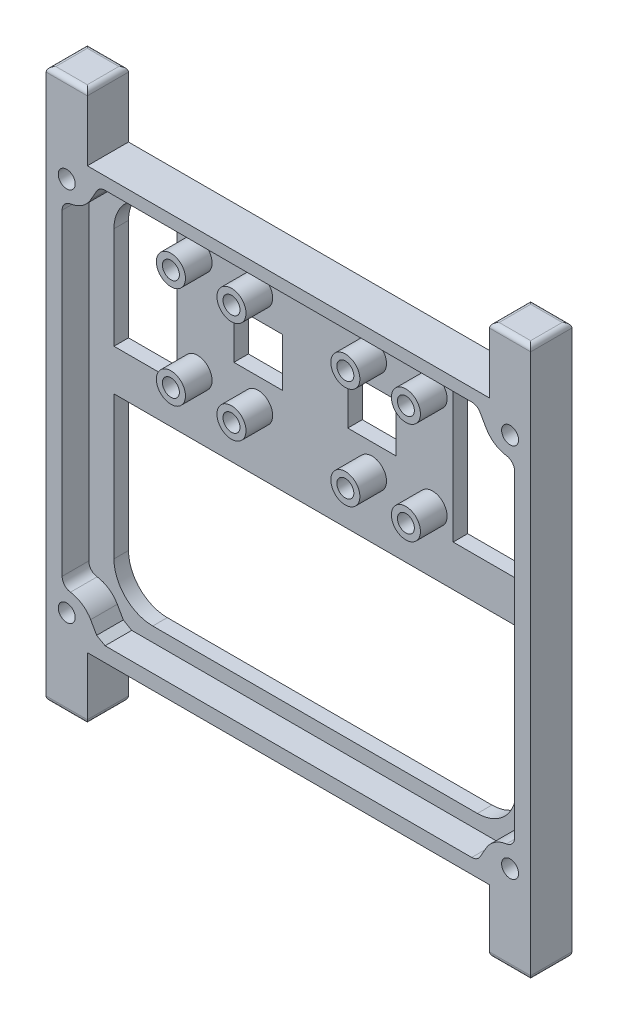
SolidWorks part; units mm, degrees
ref_plane "Front Plane" through (0, 0, 0) normal (0, 0, 1) x (1, 0, 0)
ref_plane "Top Plane" through (0, 0, 0) normal (0, 1, 0) x (1, 0, 0)
ref_plane "Right Plane" through (0, 0, 0) normal (1, 0, 0) x (0, 0, -1)
sketch "Sketch1" plane through (0, 0, 0) normal (0, 0, 1) x (1, 0, 0)
  line L1 (-50, 56.75) -> (50, 56.75)
  line L2 (-50, 56.75) -> (-50, -56.75)
  line L3 (-50, -56.75) -> (50, -56.75)
  line L4 (50, 56.75) -> (50, -56.75)
  line L5 (-50, 56.75) -> (50, -56.75) construction
  line L6 (-50, -56.75) -> (50, 56.75) construction
  point P0 (0, 0)
  dimension "D1" = 100
  dimension "D2" = 113.5
extrude "Boss-Extrude1" add sketch "Sketch1" along normal blind 8.5
sketch "Sketch2" plane through (0, 0, 8.5) normal (0, 0, 1) x (1, 0, 0)
  line L1 (50, 56.75) -> (-50, 56.75) construction
  line L2 (-41.5, 56.75) -> (-41.5, 43.25)
  line L3 (-50, -56.75) -> (50, -56.75) construction
  line L6 (0, -4.675) -> (0, 4.675) construction
  line L8 (41.5, 56.75) -> (41.5, 43.25)
  line L11 (-33.5, -37.75) -> (33.5, -37.75)
  line L12 (-41.5, 43.25) -> (41.5, 43.25)
  line L17 (-41.5, -0.25) -> (41.5, -0.25)
  line L18 (-41.5, -43.75) -> (41.5, -43.75)
  line L19 (-41.5, -29.75) -> (-41.5, -0.25)
  line L20 (41.5, -29.75) -> (41.5, -0.25)
  line L33 (41.5, -0.25) -> (41.5, -29.75)
  line L34 (-41.5, -0.25) -> (-41.5, -29.75)
  line L35 (-41.5, -43.75) -> (-41.5, -56.75)
  line L36 (41.5, -43.75) -> (41.5, -56.75)
  line L37 (-16.75, 27.75) -> (-6.75, 27.75)
  line L38 (-18.25, 29.25) -> (-5.25, 29.25)
  line L39 (-18.25, 29.25) -> (-18.25, 16.25)
  line L40 (-18.25, 16.25) -> (-5.25, 16.25)
  line L41 (-5.25, 29.25) -> (-5.25, 16.25)
  line L42 (-18.25, 29.25) -> (-5.25, 16.25) construction
  line L43 (-18.25, 16.25) -> (-5.25, 29.25) construction
  line L44 (-6.75, 27.75) -> (-6.75, 17.75)
  line L45 (-16.75, 17.75) -> (-6.75, 17.75)
  line L46 (-16.75, 27.75) -> (-16.75, 17.75)
  line L47 (-41.5, -56.75) -> (41.5, -56.75)
  line L48 (-41.5, 56.75) -> (41.5, 56.75)
  line L49 (50, -56.75) -> (50, 56.75) construction
  line L50 (4.675, 0) -> (-4.675, 0) construction
  line L51 (0, 43.25) -> (0, 0) construction
  line L52 (-11.75, 35.783) -> (-11.75, 12.7164) construction
  line L57 (16.75, 27.75) -> (16.75, 17.75)
  line L58 (16.75, 17.75) -> (6.75, 17.75)
  line L59 (6.75, 27.75) -> (6.75, 17.75)
  line L60 (16.75, 27.75) -> (6.75, 27.75)
  line L61 (28.5, 37.25) -> (23.5, 37.25)
  line L62 (23.5, 37.25) -> (23.5, 11.25)
  line L63 (41.5, 11.25) -> (23.5, 11.25)
  line L64 (41.5, 24.25) -> (41.5, 11.25)
  line L65 (6.75, 27.75) -> (16.75, 27.75)
  line L66 (16.75, 17.75) -> (6.75, 17.75)
  line L67 (23.5, 37.25) -> (23.5, 11.25)
  line L68 (41.5, 11.25) -> (41.5, 24.25)
  line L69 (23.5, 37.25) -> (28.5, 37.25)
  arc A0 (41.5, -29.75) -> (33.5, -37.75) centre (33.5, -29.75) cw
  arc A1 (-41.5, -29.75) -> (-33.5, -37.75) centre (-33.5, -29.75) ccw
  circle A4 centre (45.75, 38.75) radius 1.75
  circle A5 centre (45.75, -38.75) radius 1.75
  circle A6 centre (-45.75, 38.75) radius 1.75
  circle A7 centre (-45.75, -38.75) radius 1.75
  arc A8 (41.5, 24.25) -> (28.5, 37.25) centre (28.5, 24.25) ccw
  arc A9 (28.5, 37.25) -> (41.5, 24.25) centre (28.5, 24.25) cw
  point P0 (45.75, 38.75)
  point P22 (-11.75, 22.75)
  point P63 (-11.75, 22.75)
  dimension "D2" = 13
  dimension "D3" = 13.5
  dimension "D6" = 113.5
  dimension "D8" = 6
  dimension "D11" = 13
  dimension "D12" = 13
  dimension "D14" = 18
  dimension "D15" = 4.25
  dimension "D13" = 1.5
extrude "Cut-Extrude1" cut sketch "Sketch2" against normal up to next
ref_plane "Plane1" through (0, 0, 3) normal (0, 0, -1) x (-1, 0, 0)
sketch "Sketch6" plane through (0, 0, 8.5) normal (0, 0, 1) x (1, 0, 0)
  line L8 (50, -56.75) -> (50, 56.75) construction
  line L10 (41.5, 8.25) -> (41.5, 29.25)
  line L11 (33.5, 8.25) -> (41.5, 8.25)
  line L14 (6.75, 17.75) -> (16.75, 17.75)
  line L15 (6.75, 27.75) -> (6.75, 17.75)
  line L16 (16.75, 27.75) -> (6.75, 27.75)
  line L17 (16.75, 17.75) -> (16.75, 27.75)
  line L21 (33.5, 37.25) -> (28.5, 37.25)
  line L22 (28.5, 37.25) -> (28.5, 8.25)
  line L23 (28.5, 8.25) -> (33.5, 8.25)
  line L24 (0, -4.675) -> (0, 4.675) construction
  line L25 (-41.5, 8.25) -> (-41.5, 29.25)
  line L26 (-33.5, 8.25) -> (-41.5, 8.25)
  line L27 (-28.5, 8.25) -> (-33.5, 8.25)
  line L28 (-28.5, 37.25) -> (-28.5, 8.25)
  line L29 (-33.5, 37.25) -> (-28.5, 37.25)
  arc A1 (41.5, 29.25) -> (33.5, 37.25) centre (33.5, 29.25) ccw
  arc A2 (-41.5, 29.25) -> (-33.5, 37.25) centre (-33.5, 29.25) cw
  dimension "D1" = 8.5
  dimension "D2" = 5
extrude "Cut-Extrude2" cut sketch "Sketch6" against normal up to next
sketch "Sketch8" plane through (0, 0, 8.5) normal (0, 0, 1) x (1, 0, 0)
  line L0 (-37.835, -40.7) -> (37.835, -40.7)
  line L1 (-41.5, -43.75) -> (41.5, -43.75) construction
  line L2 (-37.835, -40.7) -> (-39.5671, -39.7)
  line L3 (-39.5671, -39.7) -> (-40.8111, -37.52)
  line L4 (0, -4.675) -> (0, 4.675) construction
  line L5 (39.5671, -39.7) -> (40.8111, -37.52)
  line L6 (4.675, 0) -> (-4.675, 0) construction
  line L7 (39.5671, 39.7) -> (40.8111, 37.52)
  line L8 (-39.5671, 39.7) -> (-40.8111, 37.52)
  line L9 (46.7011, 32.72) -> (46.7011, -32.72)
  line L10 (-46.7011, -32.72) -> (-46.7011, 32.72)
  line L11 (-37.835, 40.7) -> (37.835, 40.7)
  arc A0 (-39.5671, -39.7) -> (-37.835, -40.7) centre (-37.845, -38.7172) ccw
  arc A1 (-44.9811, -34.7) -> (-40.8111, -37.52) centre (-45.7922, -40.3925) cw
  arc A2 (-46.7011, -32.72) -> (-44.9811, -34.7) centre (-44.7011, -32.7197) ccw
  arc A3 (39.5671, -39.7) -> (37.835, -40.7) centre (37.845, -38.7172) cw
  arc A4 (44.9811, -34.7) -> (40.8111, -37.52) centre (45.7922, -40.3925) ccw
  arc A5 (46.7011, -32.72) -> (44.9811, -34.7) centre (44.7011, -32.7197) cw
  arc A6 (39.5671, 39.7) -> (37.835, 40.7) centre (37.845, 38.7172) ccw
  arc A7 (46.7011, 32.72) -> (44.9811, 34.7) centre (44.7011, 32.7197) ccw
  arc A8 (44.9811, 34.7) -> (40.8111, 37.52) centre (45.7922, 40.3925) cw
  arc A9 (-39.5671, 39.7) -> (-37.835, 40.7) centre (-37.845, 38.7172) cw
  arc A10 (-44.9811, 34.7) -> (-40.8111, 37.52) centre (-45.7922, 40.3925) ccw
  arc A11 (-46.7011, 32.72) -> (-44.9811, 34.7) centre (-44.7011, 32.7197) cw
  point P4 (0, -40.7)
  point P5 (0, -43.75)
  point P8 (-44.9811, -34.7)
  point P10 (-46.7011, -32.72)
  dimension "D5" = 2.51
  dimension "D9" = 1.98
  dimension "D1" = 3.05
  dimension "D2" = 75.67
  dimension "D3" = 2
  dimension "D4" = 1
  dimension "D6" = 2.18
  dimension "D7" = 2.82
  dimension "D8" = 4.17
  dimension "D10" = 1.72
extrude "Cut-Extrude4" cut sketch "Sketch8" against normal blind 5.5
sketch "Sketch7" plane through (0, 0, 8.5) normal (0, 0, 1) x (1, 0, 0)
  line L0 (-16.75, 27.75) -> (-6.75, 27.75) construction
  line L3 (0, 40.7) -> (0, 35.089)
  line L4 (-37.835, 40.7) -> (37.835, 40.7) construction
  circle A0 centre (-11.75, 33.25) radius 3
  circle A1 centre (-11.75, 33.25) radius 1.75
  circle A2 centre (-11.75, 12.25) radius 1.75
  circle A3 centre (-11.75, 12.25) radius 3
  circle A4 centre (11.75, 33.25) radius 1.75
  circle A5 centre (11.75, 33.25) radius 3
  circle A6 centre (11.75, 12.25) radius 1.75
  circle A7 centre (11.75, 12.25) radius 3
  circle A8 centre (-24.25, 33.25) radius 3
  circle A9 centre (-24.25, 33.25) radius 1.75
  circle A10 centre (-24.25, 12.25) radius 3
  circle A11 centre (-24.25, 12.25) radius 1.75
  circle A12 centre (24.25, 12.25) radius 1.75
  circle A13 centre (24.25, 12.25) radius 3
  circle A14 centre (24.25, 33.25) radius 1.75
  circle A15 centre (24.25, 33.25) radius 3
  point P0 (-11.75, 33.25)
  point P6 (-11.75, 27.75)
  point P25 (-24.25, 33.25)
  dimension "D2" = 12.5
  dimension "D1" = 5.5
extrude "Boss-Extrude3" add sketch "Sketch7" against normal blind 5.5 contours A8 A9 | A10 A11 | A3 A2 | A5 A4 | A15 A14 | A7 A6 | A13 A12 | A0 A1
fillet "Fillet1" radius 1 16 edges at (45.75, 56.75, 8.5) (50, 56.75, 4.25) (45.75, 56.75, 0) (41.5, 56.75, 4.25) (-41.5, 56.75, 4.25) (-45.75, 56.75, 0) (-50, 56.75, 4.25) (-45.75, 56.75, 8.5) (-50, -56.75, 4.25) (-45.75, -56.75, 8.5) (-41.5, -56.75, 4.25) (-45.75, -56.75, 0) (45.75, -56.75, 8.5) (41.5, -56.75, 4.25) (45.75, -56.75, 0) (50, -56.75, 4.25)
